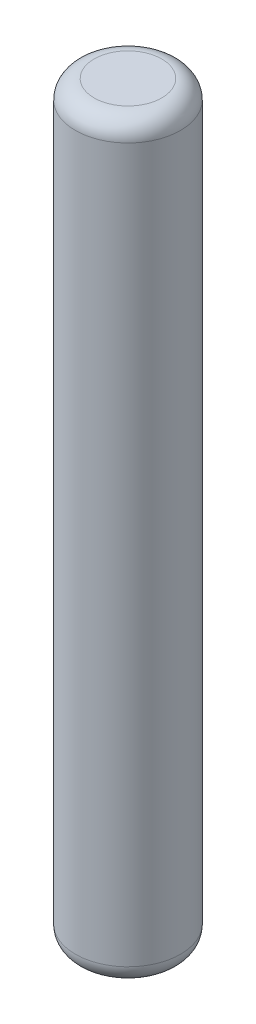
SolidWorks part; units mm, degrees
ref_plane "Front Plane" through (0, 0, 0) normal (0, 0, 1) x (1, 0, 0)
ref_plane "Top Plane" through (0, 0, 0) normal (0, 1, 0) x (1, 0, 0)
ref_plane "Right Plane" through (0, 0, 0) normal (1, 0, 0) x (0, 0, -1)
sketch "Sketch1" plane through (0, 0, 0) normal (0, 1, 0) x (1, 0, 0)
  circle A0 centre (0, 0) radius 1.778
  dimension "D1" = 3.556
extrude "Boss-Extrude1" add sketch "Sketch1" along normal blind 25.4
fillet "Fillet2" radius 0.635 2 edges at (0, 0, 1.778) (0, 25.4, 1.778)
